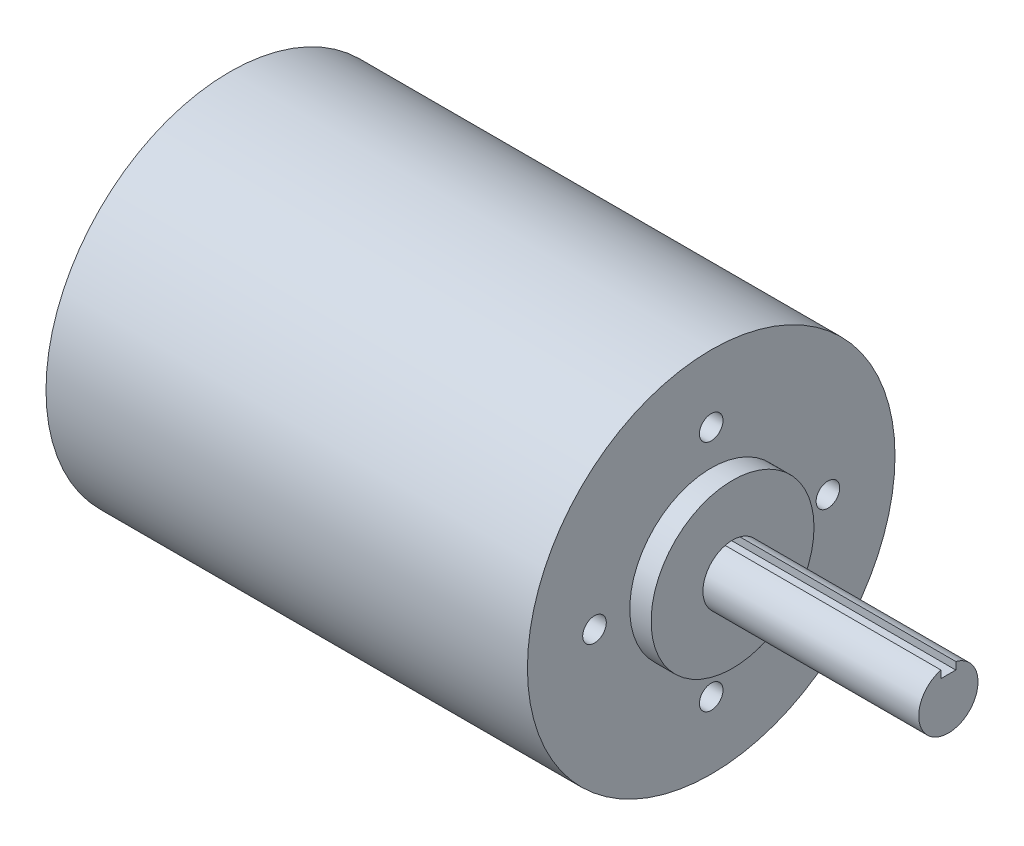
SolidWorks part; units mm, degrees
ref_plane "Front Plane" through (0, 0, 0) normal (0, 0, 1) x (1, 0, 0)
ref_plane "Top Plane" through (0, 0, 0) normal (0, 1, 0) x (1, 0, 0)
ref_plane "Right Plane" through (0, 0, 0) normal (1, 0, 0) x (0, 0, -1)
sketch "Sketch1" plane through (0, 0, 0) normal (1, 0, 0) x (0, 0, -1)
  circle A0 centre (0, 0) radius 39.37
  dimension "D1" = 78.74
extrude "Boss-Extrude1" add sketch "Sketch1" along normal blind 103.124
sketch "Sketch2" plane through (103.124, 0, 0) normal (1, 0, 0) x (0, 0, -1)
  line L0 (-1.5875, 6.1484) -> (-1.5875, 4.5609)
  line L1 (-1.5875, 4.5609) -> (1.5875, 4.5609)
  line L2 (0, 4.5609) -> (0, 0) construction
  line L3 (1.5875, 6.1484) -> (1.5875, 4.5609)
  arc A0 (-1.5875, 6.1484) -> (1.5875, 6.1484) centre (0, 0) ccw
  dimension "D1" = 12.7
  dimension "D2" = 3.175
  dimension "D3" = 1.5875
extrude "Boss-Extrude2" add sketch "Sketch2" along normal blind 50.8
hole_wizard "#8 (0.199) Diameter Hole1" positions "Sketch5" profile "Sketch4" hole size "#8" standard "Ansi Inch"
sketch "Sketch5" plane through (103.124, 0, 0) normal (1, 0, 0) x (0, 0, -1)
  point P0 (0, 25)
  dimension "D1" = 25
sketch "Sketch4" plane through (103.124, 25, 0) normal (0, 1, 0) x (0, 0, -1)
  line L0 (0, 0) -> (0, 11.5186)
  line L1 (0, 11.5186) -> (2.5273, 10)
  line L2 (2.5273, 10) -> (2.5273, 0)
  line L5 (2.5273, 0) -> (0, 0)
  line L10 (0, 11.5186) -> (-2.5273, 10) construction
  line L11 (0, -6.35) -> (0, 107.95) construction
  dimension "Hole Dia." = 5.0546
  dimension "Hole Depth" = 10
  dimension "Drill Angle" = 118
pattern_circular "CirPattern1" count 4 every 90 about axis through (0, 0, 0) along (1, 0, 0) of "#8 (0.199) Diameter Hole1"
sketch "Sketch6" plane through (103.124, 0, 0) normal (1, 0, 0) x (0, 0, -1)
  circle A0 centre (0, 0) radius 6.35
  circle A1 centre (0, 0) radius 17.4498
  dimension "D1" = 12.7
  dimension "D2" = 34.8996
extrude "Boss-Extrude3" add sketch "Sketch6" along normal blind 4.572
